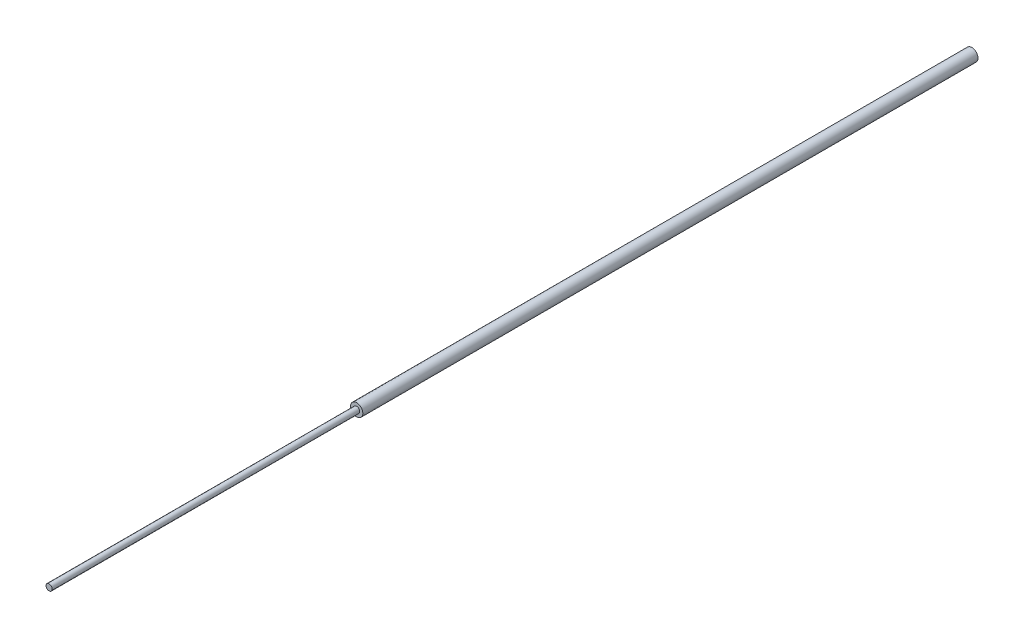
SolidWorks part; units mm, degrees
ref_plane "Plan de face" through (0, 0, 0) normal (0, 0, 1) x (1, 0, 0)
ref_plane "Plan de dessus" through (0, 0, 0) normal (0, 1, 0) x (1, 0, 0)
ref_plane "Plan de droite" through (0, 0, 0) normal (1, 0, 0) x (0, 0, -1)
sketch "Esquisse1" plane through (0, 0, 0) normal (0, 0, 1) x (1, 0, 0)
  circle A0 centre (0, 0) radius 3
  dimension "D1" = 6
extrude "Boss.-Extru.1" add sketch "Esquisse1" along normal blind 300
sketch "Esquisse2" plane through (0, 0, 300) normal (0, 0, 1) x (1, 0, 0)
  circle A0 centre (0, 0) radius 1.5
  dimension "D1" = 3
extrude "Boss.-Extru.2" add sketch "Esquisse2" along normal blind 150
